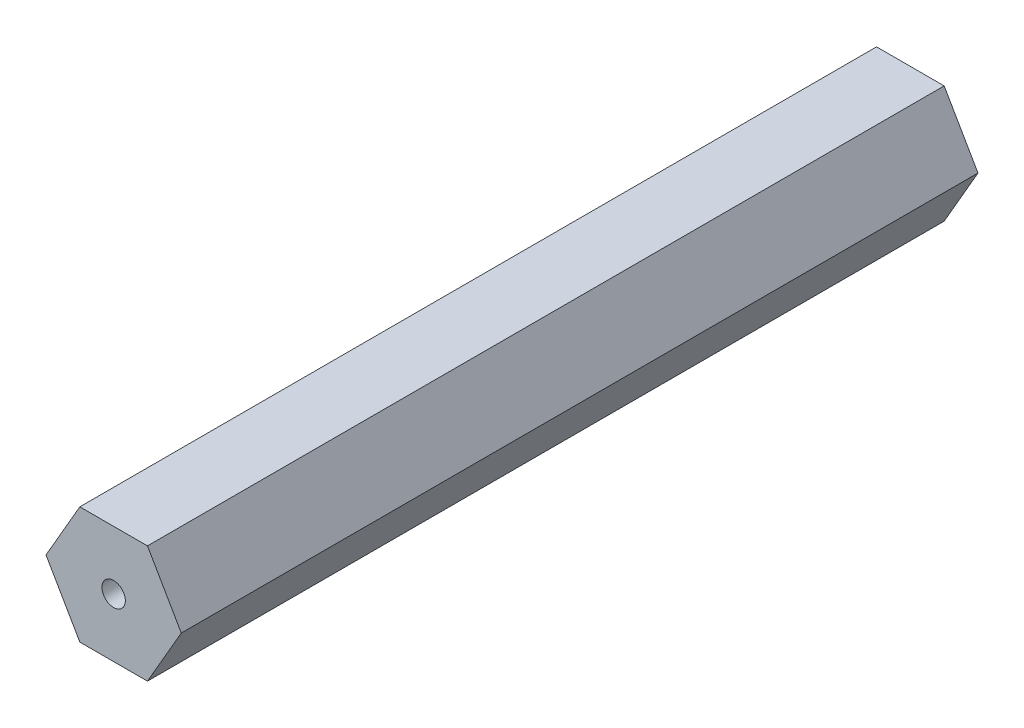
SolidWorks part; units mm, degrees
ref_plane "Front Plane" through (0, 0, 0) normal (0, 0, 1) x (1, 0, 0)
ref_plane "Top Plane" through (0, 0, 0) normal (0, 1, 0) x (1, 0, 0)
ref_plane "Right Plane" through (0, 0, 0) normal (1, 0, 0) x (0, 0, -1)
sketch "Sketch1" plane through (0, 0, 0) normal (0, 0, 1) x (1, 0, 0)
  line L1 (8.4354, 1.1842) -> (4.7693, 7.5342)
  line L2 (4.7693, 7.5342) -> (-2.5631, 7.5342)
  line L3 (-2.5631, 7.5342) -> (-6.2293, 1.1842)
  line L4 (-6.2293, 1.1842) -> (-2.5631, -5.1658)
  line L5 (-2.5631, -5.1658) -> (4.7693, -5.1658)
  line L6 (4.7693, -5.1658) -> (8.4354, 1.1842)
  circle A0 centre (1.1031, 1.1842) radius 6.35 construction
  circle A1 centre (1.1031, 1.1842) radius 1.27
  dimension "D1" = 12.7
extrude "Boss-Extrude1" add sketch "Sketch1" along normal blind 86.36
